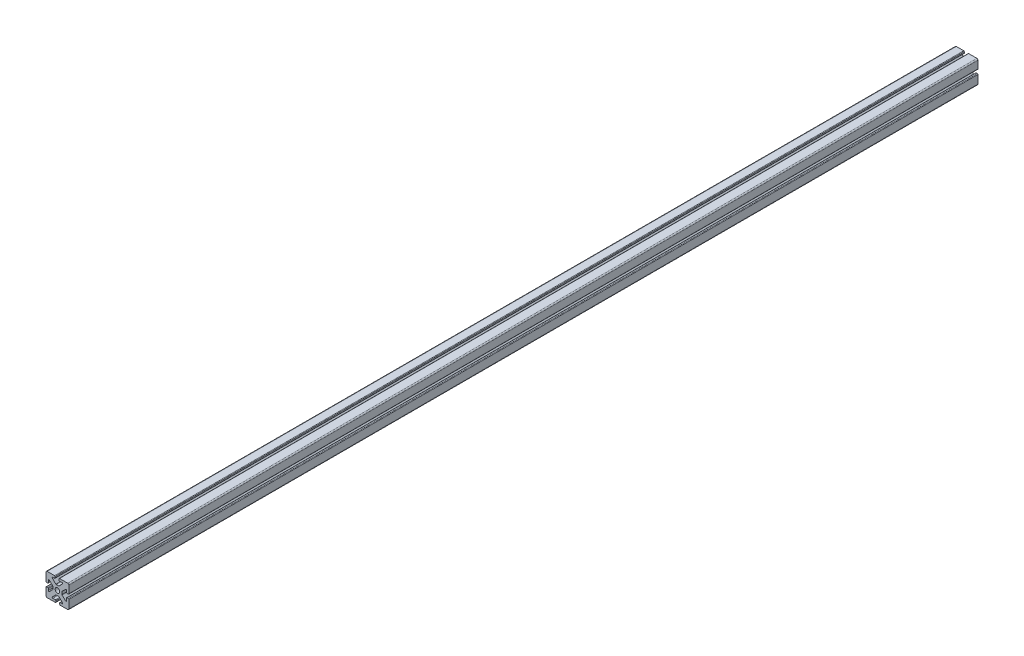
SolidWorks part; units mm, degrees
ref_plane "Front" through (0, 0, 0) normal (0, 0, 1) x (1, 0, 0)
ref_plane "Top" through (0, 0, 0) normal (0, 1, 0) x (1, 0, 0)
ref_plane "Right" through (0, 0, 0) normal (1, 0, 0) x (0, 0, -1)
sketch "草图1" plane through (0, 0, 0) normal (0, 0, 1) x (1, 0, 0)
  line L1 (-20, 20) -> (20, 20)
  line L2 (-20, 20) -> (-20, -20)
  line L3 (-20, -20) -> (20, -20)
  line L4 (20, 20) -> (20, -20)
  line L5 (-20, 20) -> (20, -20) construction
  line L6 (-20, -20) -> (20, 20) construction
  point P0 (0, 0)
  dimension "D1" = 40
extrude "凸台-拉伸1" add sketch "草图1" along normal blind 1593
sketch "草图2" plane through (0, 0, 1593) normal (0, 0, 1) x (1, 0, 0)
  circle A0 centre (0, 0) radius 4.05
  dimension "D1" = 8.1
extrude "切除-拉伸1" cut sketch "草图2" against normal blind 10000
sketch "草图4" plane through (0, 0, 1593) normal (0, 0, 1) x (1, 0, 0)
  line L0 (20, -20) -> (20, 20) construction
  line L1 (20, 0) -> (20, 4)
  line L2 (20, 0) -> (20, -2.652)
  line L3 (7.8769, 2.6) -> (7.8769, -2.6)
  line L4 (20, 4) -> (16, 4)
  line L5 (20, -2.652) -> (16, -2.652)
  line L6 (16, 10.5) -> (16, 4)
  line L7 (16, 10.5) -> (7.8769, 2.6)
  line L8 (16, -10.5) -> (7.8769, -2.6)
  line L9 (16, -2.652) -> (16, -10.5)
  point P11 (7.8769, 0)
  point P12 (16, 0)
extrude "切除-拉伸2" cut sketch "草图4" against normal blind 10000
fillet "圆角1" radius 1 8 edges at (16, 10.5, 796.5) (16, -10.5, 796.5) (7.8769, 2.6, 796.5) (20, -2.652, 796.5) (16, -2.652, 796.5) (20, 4, 796.5) (16, 4, 796.5) (7.8769, -2.6, 796.5)
pattern_circular "阵列(圆周)2" count 4 over 360 about axis through (0, 0, 0) along (0, 0, 1) of "切除-拉伸2"
fillet "圆角2" radius 1 8 edges at (10.5, 16, 796.5) (-10.5, 16, 796.5) (-4, 20, 796.5) (2.652, 16, 796.5) (2.652, 20, 796.5) (-2.6, 7.8769, 796.5) (-4, 16, 796.5) (2.6, 7.8769, 796.5)
fillet "圆角3" radius 1 8 edges at (-7.8769, -2.6, 796.5) (-7.8769, 2.6, 796.5) (-20, 2.652, 796.5) (-16, 10.5, 796.5) (-20, -4, 796.5) (-16, -4, 796.5) (-16, -10.5, 796.5) (-16, 2.652, 796.5)
fillet "圆角4" radius 1 8 edges at (4, -20, 796.5) (4, -16, 796.5) (10.5, -16, 796.5) (-2.652, -20, 796.5) (2.6, -7.8769, 796.5) (-2.6, -7.8769, 796.5) (-2.652, -16, 796.5) (-10.5, -16, 796.5)
fillet "圆角5" radius 2 4 edges at (-20, -20, 796.5) (20, -20, 796.5) (-20, 20, 796.5) (20, 20, 796.5)
